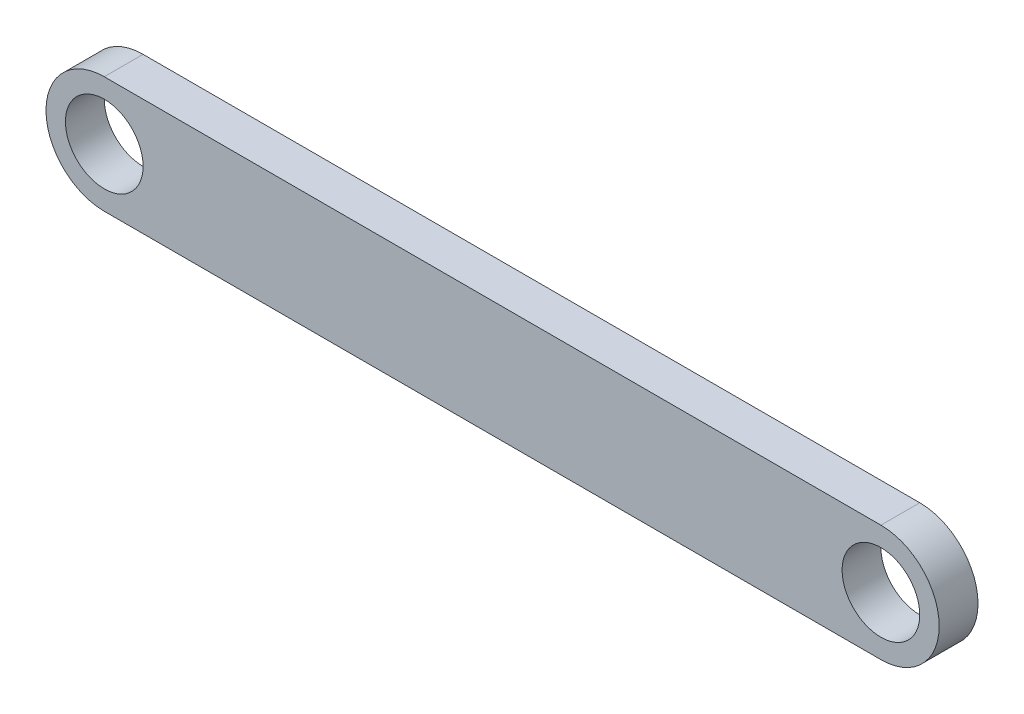
SolidWorks part; units mm, degrees
ref_plane "Front Plane" through (0, 0, 0) normal (0, 0, 1) x (1, 0, 0)
ref_plane "Top Plane" through (0, 0, 0) normal (0, 1, 0) x (1, 0, 0)
ref_plane "Right Plane" through (0, 0, 0) normal (1, 0, 0) x (0, 0, -1)
sketch "Sketch1" plane through (0, 0, 0) normal (0, 0, 1) x (1, 0, 0)
  line L0 (-100, 0) -> (100, 0)
  line L1 (100, 0) -> (100, -30)
  line L2 (100, -30) -> (-100, -30)
  line L3 (-100, -30) -> (-100, 0)
  point P3 (0, 0)
  dimension "D1" = 200
  dimension "D2" = 30
extrude "Boss-Extrude1" add sketch "Sketch1" along normal blind 10
sketch "Sketch3" plane through (0, 0, 10) normal (0, 0, 1) x (1, 0, 0)
  line L0 (-100, 0) -> (-100, -30) construction
  line L1 (100, -30) -> (100, 0) construction
  line L2 (-100, 0) -> (-100, -30)
  line L3 (100, 0) -> (100, -30)
  arc A0 (-100, 0) -> (-100, -30) centre (-100, -15) ccw
  arc A1 (100, -30) -> (100, 0) centre (100, -15) ccw
extrude "Boss-Extrude2" add sketch "Sketch3" against normal blind 10
sketch "Sketch4" plane through (0, 0, 10) normal (0, 0, 1) x (1, 0, 0)
  line L0 (100, 0) -> (-100, 0) construction
  line L1 (-115, -15) -> (-115, 3.8307) construction
  line L2 (-100, -15) -> (-100, 5.382) construction
  line L3 (0, 33.6013) -> (0, -54.9999) construction
  circle A0 centre (-100, -15) radius 10
  arc A1 (-100, 0) -> (-100, -30) centre (-100, -15) ccw construction
  circle A2 centre (100, -15) radius 10
  dimension "D1" = 20
  dimension "D2" = 15
  dimension "D3" = 15
extrude "Cut-Extrude2" cut sketch "Sketch4" against normal blind 10
